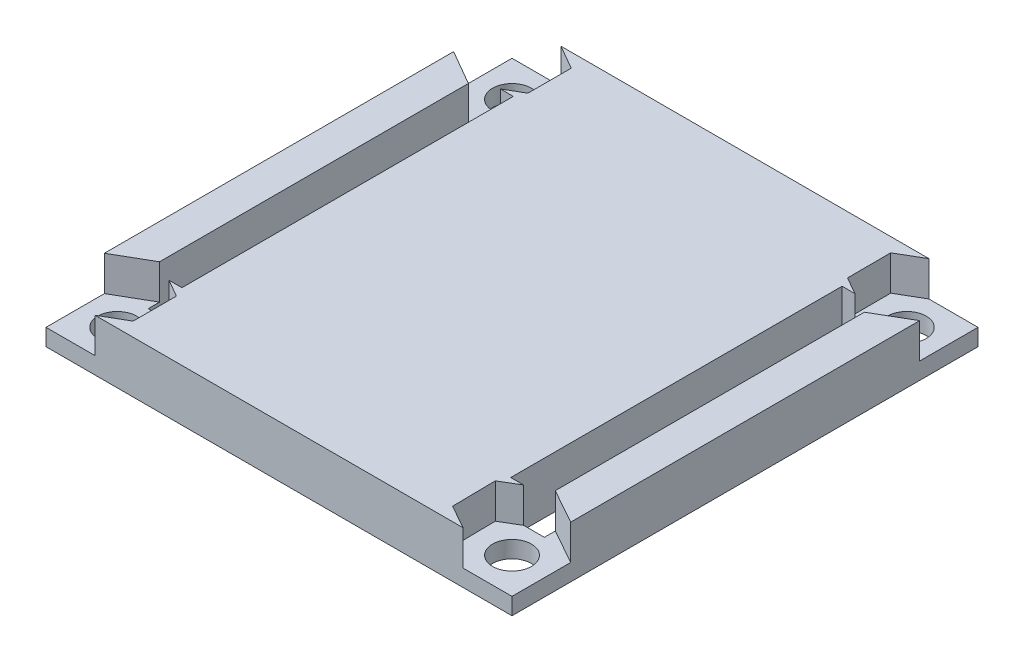
SolidWorks part; units mm, degrees
material "ABS"
ref_plane "Front Plane" through (0, 0, 0) normal (0, 0, 1) x (1, 0, 0)
ref_plane "Top Plane" through (0, 0, 0) normal (0, 1, 0) x (1, 0, 0)
ref_plane "Right Plane" through (0, 0, 0) normal (1, 0, 0) x (0, 0, -1)
sketch "Sketch1" plane through (0, 0, 0) normal (0, 1, 0) x (1, 0, 0)
  line L1 (-18, -18) -> (18, -18)
  line L2 (-18, -18) -> (-18, 18)
  line L3 (-18, 18) -> (18, 18)
  line L4 (18, -18) -> (18, 18)
  line L5 (-18, -18) -> (18, 18) construction
  line L6 (-18, 18) -> (18, -18) construction
  point P0 (0, 0)
  dimension "D1" = 36
  dimension "D2" = 36
extrude "Boss-Extrude1" add sketch "Sketch1" along normal blind 4
sketch "Sketch2" plane through (0, 4, 0) normal (0, 1, 0) x (1, 0, 0)
  line L1 (15.25, -15.25) -> (-15.25, -15.25) construction
  line L2 (15.25, -15.25) -> (15.25, 15.25) construction
  line L3 (15.25, 15.25) -> (-15.25, 15.25) construction
  line L4 (-15.25, -15.25) -> (-15.25, 15.25) construction
  line L5 (15.25, -15.25) -> (-15.25, 15.25) construction
  line L6 (15.25, 15.25) -> (-15.25, -15.25) construction
  circle A0 centre (-15.25, 15.25) radius 1.5
  circle A1 centre (15.25, 15.25) radius 1.5
  circle A2 centre (15.25, -15.25) radius 1.5
  circle A3 centre (-15.25, -15.25) radius 1.5
  point P0 (0, 0)
  dimension "D3" = 3
  dimension "D1" = 30.5
  dimension "D2" = 30.5
extrude "Cut-Extrude1" cut sketch "Sketch2" against normal through all
sketch "Sketch3" plane through (0, 4, 0) normal (0, 1, 0) x (1, 0, 0)
  line L0 (-15.25, 15.25) -> (-15.25, 18.5986) construction
  line L1 (-15.25, 11.9014) -> (-12.35, 13.5757)
  line L2 (-12.35, 13.5757) -> (-12.35, 16.9243)
  line L3 (-12.35, 16.9243) -> (-15.25, 18.5986)
  line L5 (-18.15, 16.9243) -> (-18.15, 13.5757)
  line L6 (-18.15, 13.5757) -> (-15.25, 11.9014)
  line L7 (15.2627, 11.9014) -> (18.1563, 13.5867)
  line L8 (18.1563, 13.5867) -> (18.1436, 16.9353)
  line L10 (15.2373, 18.5986) -> (12.3437, 16.9133)
  line L11 (12.3437, 16.9133) -> (12.3564, 13.5647)
  line L12 (12.3564, 13.5647) -> (15.2627, 11.9014)
  line L14 (18.1742, -16.8817) -> (18.1252, -13.5334)
  line L15 (18.1252, -13.5334) -> (15.201, -11.9017)
  line L16 (15.201, -11.9017) -> (12.3258, -13.6183)
  line L17 (12.3258, -13.6183) -> (12.3748, -16.9666)
  line L18 (12.3748, -16.9666) -> (15.299, -18.5983)
  line L19 (-15.25, -18.5986) -> (-12.35, -16.9243)
  line L20 (-12.35, -16.9243) -> (-12.35, -13.5757)
  line L21 (-12.35, -13.5757) -> (-15.25, -11.9014)
  line L22 (-15.25, -11.9014) -> (-18.15, -13.5757)
  line L23 (-18.15, -13.5757) -> (-18.15, -16.9243)
  line L25 (-15.25, 18.5986) -> (-18.15, 18.5986)
  line L26 (-18.15, 18.5986) -> (-18.15, 16.9243)
  line L27 (15.2373, 18.5986) -> (18.1436, 18.5986)
  line L28 (18.1436, 18.5986) -> (18.1436, 16.9353)
  line L29 (18.1742, -16.8817) -> (18.1742, -18.5983)
  line L30 (18.1742, -18.5983) -> (15.299, -18.5983)
  line L31 (-18.15, -16.9243) -> (-18.15, -18.5986)
  line L32 (-18.15, -18.5986) -> (-15.25, -18.5986)
  line L34 (-16.7, -17.7615) -> (-15.25, -18.5986) [skipped]
  line L35 (15.299, -18.5983) -> (16.7366, -17.74) [skipped]
  line L36 (16.6905, 17.767) -> (15.2373, 18.5986) [skipped]
  line L37 (-15.25, 18.5986) -> (-16.7, 17.7615) [skipped]
  circle A0 centre (-15.25, 15.25) radius 2.9 construction
  circle A1 centre (15.25, 15.25) radius 2.9 construction
  circle A2 centre (15.25, -15.25) radius 2.9 construction
  circle A3 centre (-15.25, -15.25) radius 2.9 construction
  dimension "D1" = 5.8
extrude "Cut-Extrude3" cut sketch "Sketch3" against normal blind 2.7
sketch "Sketch4" plane through (0, 0, 0) normal (0, -1, 0) x (1, 0, 0)
  line L0 (0, 0) -> (-14, 0) construction
  line L2 (0, -18) -> (0, 18) construction
  line L3 (-12.7, -12.8) -> (-15.3, -12.8)
  line L4 (-12.7, -12.8) -> (-12.7, 12.8)
  line L5 (-12.7, 12.8) -> (-15.3, 12.8)
  line L6 (-15.3, -12.8) -> (-15.3, 12.8)
  line L7 (-12.7, -12.8) -> (-15.3, 12.8) construction
  line L8 (-12.7, 12.8) -> (-15.3, -12.8) construction
  line L9 (18, -18) -> (-18, -18) construction
  line L10 (-18, 18) -> (18, 18) construction
  line L11 (12.7, 12.8) -> (15.3, 12.8)
  line L12 (15.3, -12.8) -> (15.3, 12.8)
  line L13 (12.7, -12.8) -> (15.3, -12.8)
  line L14 (12.7, -12.8) -> (12.7, 12.8)
  dimension "D1" = 14
  dimension "D2" = 2.6
  dimension "D3" = 25.6
extrude "Cut-Extrude4" cut sketch "Sketch4" against normal up to next
